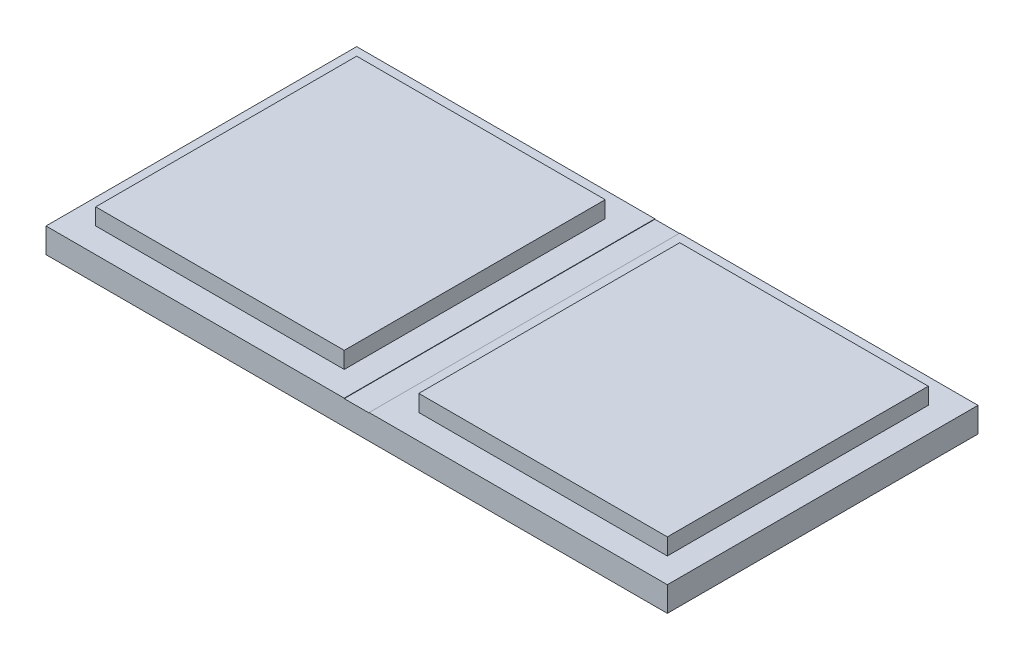
SolidWorks part; units mm, degrees
ref_plane "Front Plane" through (0, 0, 0) normal (0, 0, 1) x (1, 0, 0)
ref_plane "Top Plane" through (0, 0, 0) normal (0, 1, 0) x (1, 0, 0)
ref_plane "Right Plane" through (0, 0, 0) normal (1, 0, 0) x (0, 0, -1)
sketch "Sketch1" plane through (0, 0, 0) normal (0, 1, 0) x (1, 0, 0)
  line L1 (-15, -7.5) -> (15, -7.5)
  line L2 (-15, -7.5) -> (-15, 7.5)
  line L3 (-15, 7.5) -> (15, 7.5)
  line L4 (15, -7.5) -> (15, 7.5)
  line L5 (-15, -7.5) -> (15, 7.5) construction
  line L6 (-15, 7.5) -> (15, -7.5) construction
  point P0 (0, 0)
  dimension "D1" = 15
  dimension "D2" = 30
extrude "Boss-Extrude1" add sketch "Sketch1" along normal blind 1.2
sketch "Sketch2" plane through (0, 1.2, 0) normal (0, 1, 0) x (1, 0, 0)
  line L0 (15, 7.5) -> (-15, 7.5) construction
  line L1 (-0.6, -7.5) -> (0.6, -7.5)
  line L2 (-0.6, -7.5) -> (-0.6, 7.5)
  line L3 (-0.6, 7.5) -> (0.6, 7.5)
  line L4 (0.6, -7.5) -> (0.6, 7.5)
  line L5 (-0.6, -7.5) -> (0.6, 7.5) construction
  line L6 (-0.6, 7.5) -> (0.6, -7.5) construction
  point P0 (0, 0)
  dimension "D1" = 1.2
extrude "Cut-Extrude1" cut sketch "Sketch2" against normal blind 0.02
sketch "Sketch3" plane through (0, 1.2, 0) normal (0, 1, 0) x (1, 0, 0)
  line L8 (-13.8, -6.3) -> (-1.8, -6.3)
  line L9 (-1.8, -6.3) -> (-1.8, 6.3)
  line L10 (-1.8, 6.3) -> (-13.8, 6.3)
  line L11 (-13.8, 6.3) -> (-13.8, -6.3)
  line L12 (-13.8, -6.3) -> (-1.8, -6.3)
  line L13 (-1.8, -6.3) -> (-1.8, 6.3)
  line L14 (-1.8, 6.3) -> (-13.8, 6.3)
  line L15 (-13.8, 6.3) -> (-13.8, -6.3)
  dimension "D1" = 1.2
extrude "Boss-Extrude2" add sketch "Sketch3" along normal blind 0.8
sketch "Sketch4" plane through (0, 1.2, 0) normal (0, 1, 0) x (1, 0, 0)
  line L8 (13.8, 6.3) -> (1.8, 6.3)
  line L9 (1.8, 6.3) -> (1.8, -6.3)
  line L10 (1.8, -6.3) -> (13.8, -6.3)
  line L11 (13.8, -6.3) -> (13.8, 6.3)
  line L12 (13.8, 6.3) -> (1.8, 6.3)
  line L13 (1.8, 6.3) -> (1.8, -6.3)
  line L14 (1.8, -6.3) -> (13.8, -6.3)
  line L15 (13.8, -6.3) -> (13.8, 6.3)
  dimension "D1" = 1.2
extrude "Boss-Extrude3" add sketch "Sketch4" along normal blind 0.8
